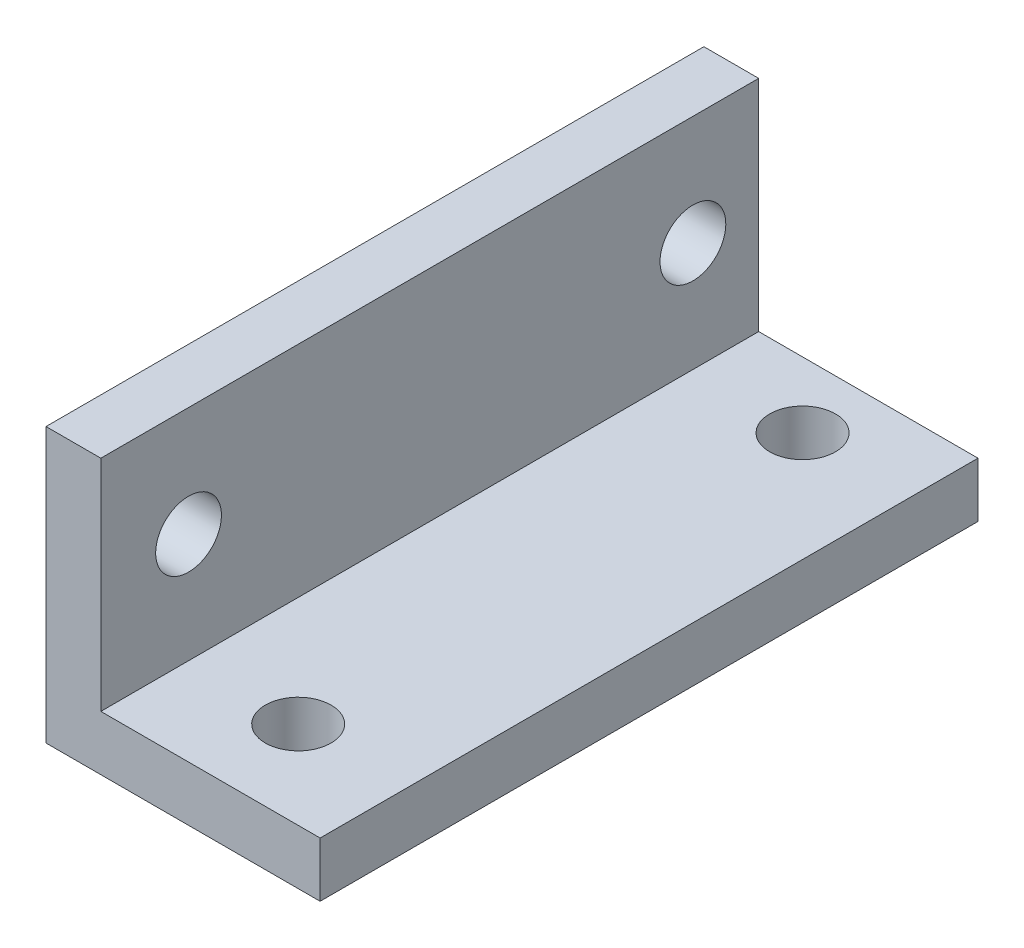
SolidWorks part; units mm, degrees
ref_plane "前视基准面" through (0, 0, 0) normal (0, 0, 1) x (1, 0, 0)
ref_plane "上视基准面" through (0, 0, 0) normal (0, 1, 0) x (1, 0, 0)
ref_plane "右视基准面" through (0, 0, 0) normal (1, 0, 0) x (0, 0, -1)
other "Configuration Table"
sketch "草图1" plane through (0, 0, 0) normal (0, 0, 1) x (1, 0, 0)
  line L0 (0, 0) -> (5, 0)
  line L1 (5, 0) -> (5, -20)
  line L2 (5, -20) -> (25, -20)
  line L3 (25, -20) -> (25, -25)
  line L4 (25, -25) -> (0, -25)
  line L5 (0, -25) -> (0, 0)
  dimension "D1" = 5
  dimension "D2" = 25
  dimension "D3" = 25
  dimension "D5" = 5
extrude "凸台-拉伸1" add sketch "草图1" along normal blind 60
sketch "草图2" plane through (0, -20, 0) normal (0, 1, 0) x (1, 0, 0)
  line L0 (25, 0) -> (5, 0) construction
  line L1 (25, -60) -> (25, 0) construction
  circle A0 centre (15, -6) radius 3
  circle A1 centre (15, -52) radius 3
  dimension "D1" = 6
  dimension "D2" = 6
  dimension "D3" = 46
  dimension "D4" = 6
  dimension "D5" = 10
extrude "切除-拉伸1" cut sketch "草图2" against normal through all
sketch "草图3" plane through (5, 0, 0) normal (1, 0, 0) x (0, 0, -1)
  line L0 (0, -20) -> (0, 0) construction
  line L1 (-60, 0) -> (0, 0) construction
  circle A0 centre (-6, -10) radius 3
  circle A1 centre (-52, -10) radius 3
  dimension "D1" = 6
  dimension "D2" = 6
  dimension "D3" = 46
  dimension "D4" = 6
  dimension "D5" = 10
  dimension "D6" = 10
extrude "切除-拉伸2" cut sketch "草图3" against normal through all
